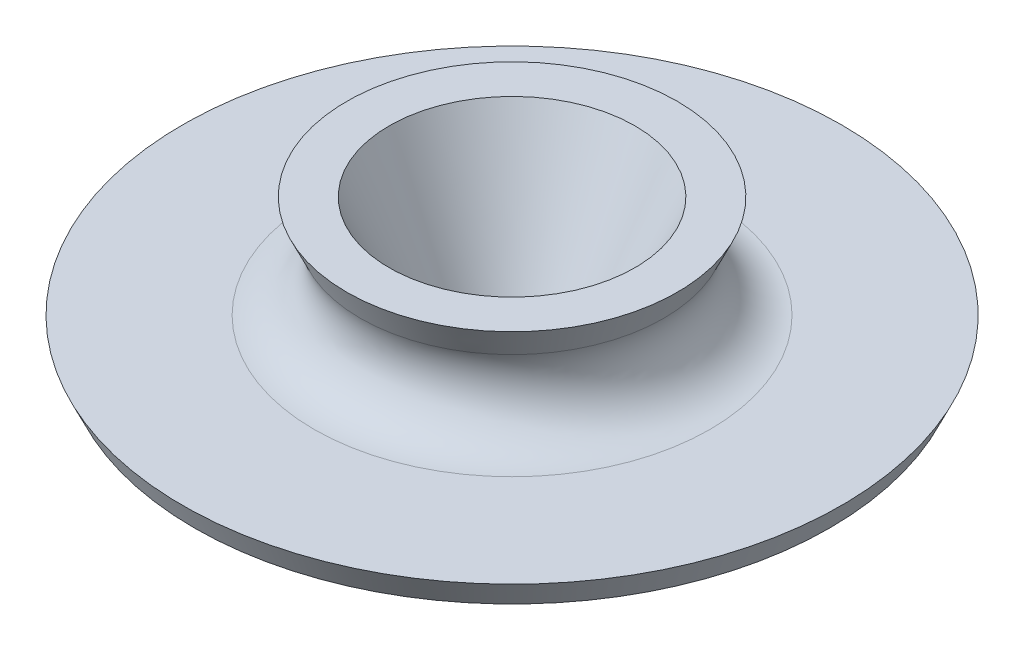
SolidWorks part; units mm, degrees
ref_plane "Front Plane" through (0, 0, 0) normal (0, 0, 1) x (1, 0, 0)
ref_plane "Top Plane" through (0, 0, 0) normal (0, 1, 0) x (1, 0, 0)
ref_plane "Right Plane" through (0, 0, 0) normal (1, 0, 0) x (0, 0, -1)
sketch "Sketch1" plane through (0, 0, 0) normal (0, 0, 1) x (1, 0, 0)
  line L0 (0, 0) -> (0, 76.3476) construction
  line L1 (-12.7, 0) -> (-19.7064, 0)
  line L2 (-19.7064, 0) -> (-22.6675, 6.35)
  line L3 (-22.6675, 6.35) -> (-78.7191, 6.35)
  line L4 (-78.7191, 6.35) -> (-81.6802, 12.7)
  line L5 (-81.6802, 12.7) -> (-29.1318, 12.7)
  line L6 (-29.1318, 12.7) -> (-40.976, 38.1)
  line L7 (-40.976, 38.1) -> (-30.4663, 38.1)
  line L8 (-30.4663, 38.1) -> (-12.7, 0)
  dimension "D1" = 38.1
  dimension "D2" = 6.35
  dimension "D3" = 6.35
  dimension "D4" = 9.525
  dimension "D5" = 6.35
  dimension "D6" = 25.4
  dimension "D7" = 57.15
  dimension "D8" = 25
revolve "Revolve1" add sketch "Sketch1" angle 360 about L0
fillet "Fillet1" radius 12.7 1 edges at (0, 12.7, -29.1318)
